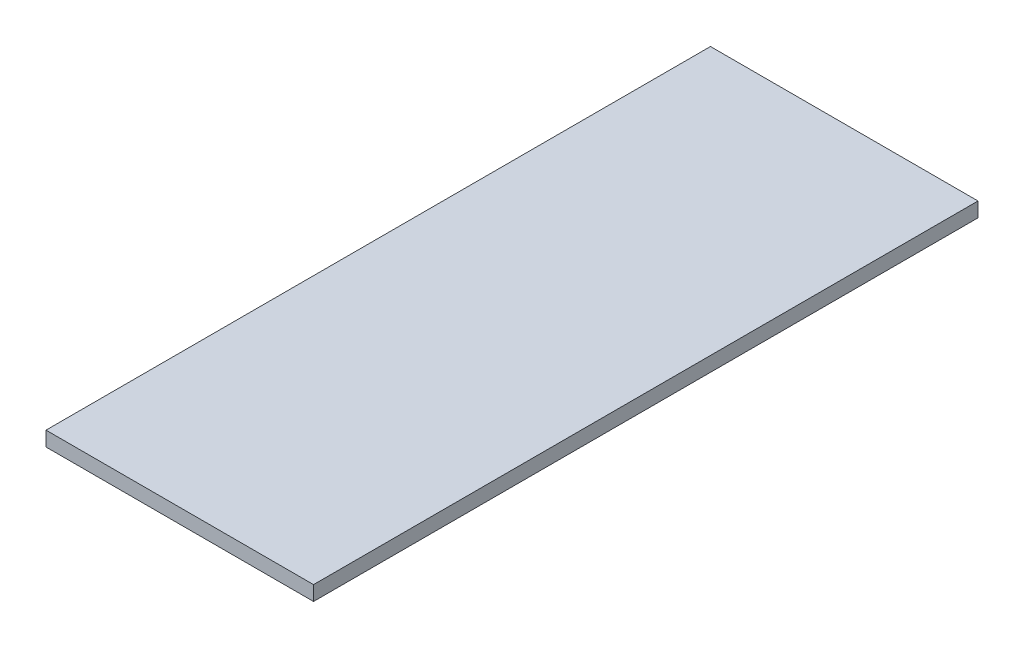
SolidWorks part; units mm, degrees
ref_plane "Спереди" through (0, 0, 0) normal (0, 0, 1) x (1, 0, 0)
ref_plane "Сверху" through (0, 0, 0) normal (0, 1, 0) x (1, 0, 0)
ref_plane "Справа" through (0, 0, 0) normal (1, 0, 0) x (0, 0, -1)
sketch "Эскиз1" plane through (0, 0, 0) normal (0, 1, 0) x (1, 0, 0)
  line L1 (-9.14, 20.4) -> (9.14, 20.4)
  line L2 (-9.14, 20.4) -> (-9.14, -25)
  line L3 (-9.14, -25) -> (9.14, -25)
  line L4 (9.14, 20.4) -> (9.14, -25)
  point P0 (0, 0)
extrude "Бобышка-Вытянуть1" add sketch "Эскиз1" along normal blind 1
